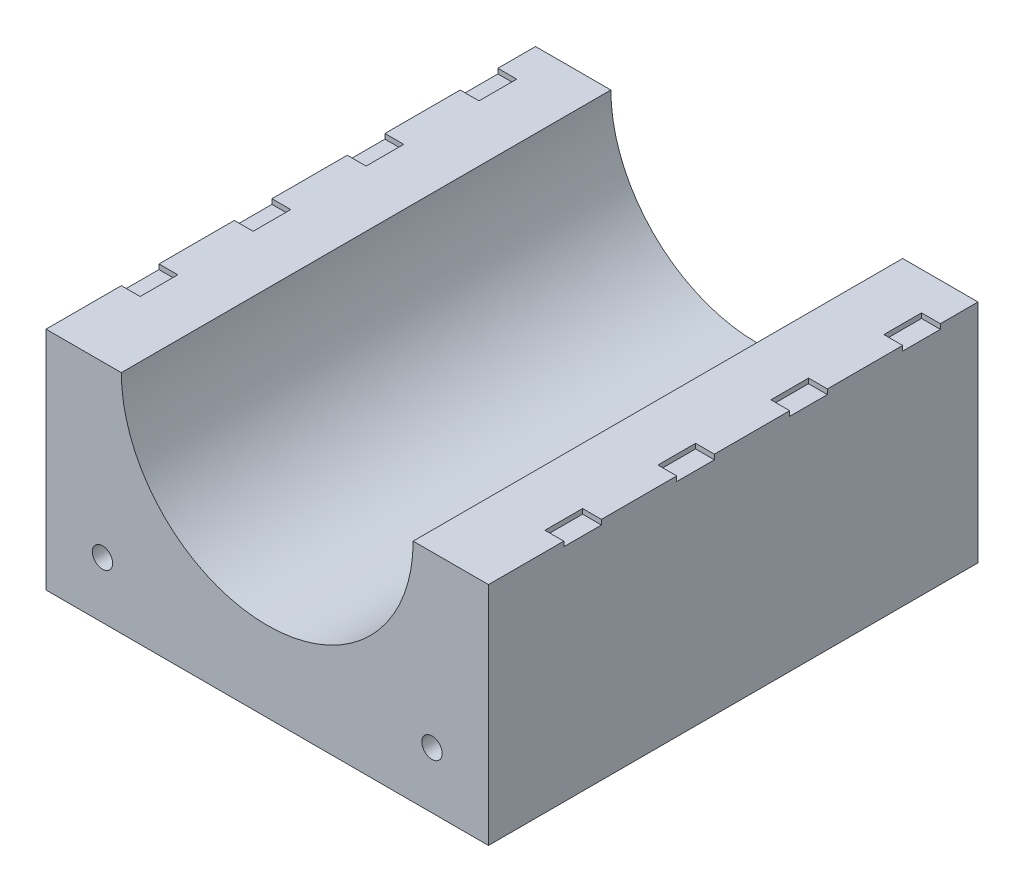
SolidWorks part; units mm, degrees
ref_plane "Front Plane" through (0, 0, 0) normal (0, 0, 1) x (1, 0, 0)
ref_plane "Top Plane" through (0, 0, 0) normal (0, 1, 0) x (1, 0, 0)
ref_plane "Right Plane" through (0, 0, 0) normal (1, 0, 0) x (0, 0, -1)
sketch "Sketch1" plane through (0, 0, 0) normal (0, 0, 1) x (1, 0, 0)
  line L0 (-49.2125, 0) -> (-74.6125, 0)
  line L1 (-74.6125, 0) -> (-74.6125, -76.2)
  line L2 (-74.6125, -76.2) -> (74.6125, -76.2)
  line L3 (74.6125, -76.2) -> (74.6125, 0)
  line L4 (74.6125, 0) -> (49.2125, 0)
  arc A0 (-49.2125, 0) -> (49.2125, 0) centre (0, 0) ccw
  circle A1 centre (-55.5625, -57.15) radius 3.429
  circle A2 centre (55.5625, -57.15) radius 3.429
  dimension "D1" = 98.425
  dimension "D5" = 6.858
  dimension "D6" = 6.858
  dimension "D2" = 25.4
  dimension "D3" = 25.4
  dimension "D4" = 76.2
  dimension "D7" = 19.05
  dimension "D8" = 19.05
  dimension "D9" = 19.05
  dimension "D10" = 19.05
extrude "Boss-Extrude1" add sketch "Sketch1" along normal blind 165.1
sketch "Sketch2" plane through (0, 0, 0) normal (0, 0, -1) x (-1, 0, 0)
  line L0 (-61.9125, 0) -> (-61.9125, -76.2) construction
  line L1 (-74.6125, 0) -> (-49.2125, 0) construction
  line L2 (74.6125, -76.2) -> (-74.6125, -76.2) construction
  line L3 (61.9125, 0) -> (61.9125, -76.2) construction
  line L4 (49.2125, 0) -> (74.6125, 0) construction
  line L5 (74.6125, -63.5) -> (-74.6125, -63.5) construction
  line L6 (74.6125, 0) -> (74.6125, -76.2) construction
  line L7 (-74.6125, -76.2) -> (-74.6125, 0) construction
  line L8 (0, -49.2125) -> (0, -76.2) construction
  line L9 (-68.3895, -12.573) -> (-55.4355, -12.573)
  line L10 (-68.3895, -12.573) -> (-68.3895, -25.527)
  line L11 (-68.3895, -25.527) -> (-55.4355, -25.527)
  line L12 (-55.4355, -12.573) -> (-55.4355, -25.527)
  line L13 (-6.477, -57.023) -> (6.477, -57.023)
  line L14 (-6.477, -57.023) -> (-6.477, -69.977)
  line L15 (-6.477, -69.977) -> (6.477, -69.977)
  line L16 (6.477, -57.023) -> (6.477, -69.977)
  line L17 (55.4355, -12.573) -> (68.3895, -12.573)
  line L18 (55.4355, -12.573) -> (55.4355, -25.527)
  line L19 (55.4355, -25.527) -> (68.3895, -25.527)
  line L20 (68.3895, -12.573) -> (68.3895, -25.527)
  line L21 (0, -57.023) -> (0, -69.977) construction
  arc A0 (-49.2125, 0) -> (49.2125, 0) centre (0, 0) ccw construction
  dimension "D1" = 12.7
  dimension "D2" = 12.954
  dimension "D3" = 12.954
  dimension "D4" = 12.954
  dimension "D5" = 12.954
  dimension "D6" = 12.954
  dimension "D7" = 12.954
  dimension "D8" = 6.477
  dimension "D9" = 12.573
  dimension "D10" = 12.573
  dimension "D11" = 6.477
  dimension "D12" = 6.477
extrude "Cut-Extrude1" cut sketch "Sketch2" against normal blind 6.35 draft 45
sketch "Sketch3" plane through (0, 0, 0) normal (0, 1, 0) x (1, 0, 0)
  line L0 (74.6125, -165.1) -> (74.6125, 0) construction
  line L1 (74.6125, -12.7) -> (68.2625, -12.7)
  line L2 (74.6125, -12.7) -> (74.6125, -25.4)
  line L3 (74.6125, -25.4) -> (68.2625, -25.4)
  line L4 (68.2625, -12.7) -> (68.2625, -25.4)
  line L5 (74.6125, 0) -> (49.2125, 0) construction
  line L6 (74.6125, -50.8) -> (68.2625, -50.8)
  line L7 (74.6125, -50.8) -> (74.6125, -63.5)
  line L8 (74.6125, -63.5) -> (68.2625, -63.5)
  line L9 (68.2625, -50.8) -> (68.2625, -63.5)
  line L10 (74.6125, -88.9) -> (68.2625, -88.9)
  line L11 (74.6125, -88.9) -> (74.6125, -101.6)
  line L12 (74.6125, -101.6) -> (68.2625, -101.6)
  line L13 (68.2625, -88.9) -> (68.2625, -101.6)
  line L14 (74.6125, -127) -> (68.2625, -127)
  line L15 (74.6125, -127) -> (74.6125, -139.7)
  line L16 (74.6125, -139.7) -> (68.2625, -139.7)
  line L17 (68.2625, -127) -> (68.2625, -139.7)
  line L18 (-68.2625, -50.8) -> (-74.6125, -50.8)
  line L19 (-68.2625, -50.8) -> (-68.2625, -63.5)
  line L20 (-68.2625, -63.5) -> (-74.6125, -63.5)
  line L21 (-74.6125, -50.8) -> (-74.6125, -63.5)
  line L22 (-68.2625, -88.9) -> (-74.6125, -88.9)
  line L23 (-68.2625, -88.9) -> (-68.2625, -101.6)
  line L24 (-68.2625, -101.6) -> (-74.6125, -101.6)
  line L25 (-74.6125, -88.9) -> (-74.6125, -101.6)
  line L26 (-68.2625, -127) -> (-74.6125, -127)
  line L27 (-68.2625, -127) -> (-68.2625, -139.7)
  line L28 (-68.2625, -139.7) -> (-74.6125, -139.7)
  line L29 (-74.6125, -127) -> (-74.6125, -139.7)
  line L30 (-68.2625, -12.7) -> (-74.6125, -12.7)
  line L31 (-68.2625, -12.7) -> (-68.2625, -25.4)
  line L32 (-68.2625, -25.4) -> (-74.6125, -25.4)
  line L33 (-74.6125, -12.7) -> (-74.6125, -25.4)
  dimension "D1" = 12.7
  dimension "D2" = 6.35
  dimension "D3" = 12.7
  dimension "D4" = 4
  dimension "D5" = 2
extrude "Cut-Extrude2" cut sketch "Sketch3" against normal blind 1.651
